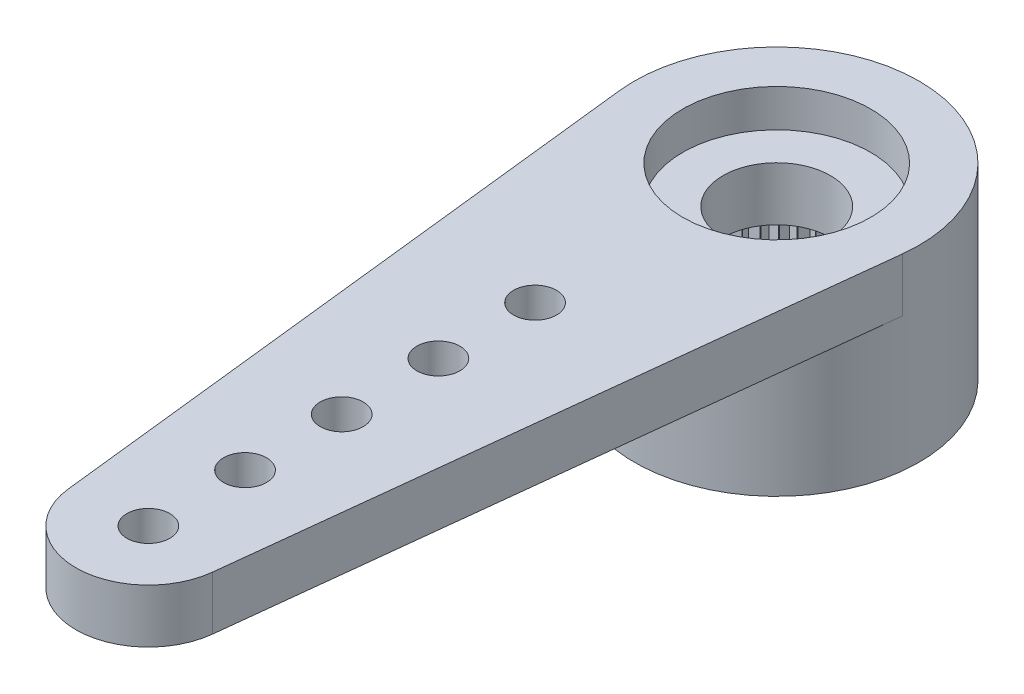
SolidWorks part; units mm, degrees
ref_plane "Front Plane" through (0, 0, 0) normal (0, 0, 1) x (1, 0, 0)
ref_plane "Top Plane" through (0, 0, 0) normal (0, 1, 0) x (1, 0, 0)
ref_plane "Right Plane" through (0, 0, 0) normal (1, 0, 0) x (0, 0, -1)
sketch "Sketch1" plane through (0, 0, 0) normal (0, 1, 0) x (1, 0, 0)
  line L0 (0, 0) -> (0, -14.859) construction
  line L1 (-1.7039, -15.0495) -> (-3.3447, -0.3739)
  line L2 (1.7039, -15.0495) -> (3.3447, -0.3739)
  arc A0 (3.3447, -0.3739) -> (-3.3447, -0.3739) centre (0, 0) ccw
  arc A1 (-1.7039, -15.0495) -> (1.7039, -15.0495) centre (0, -14.859) ccw
  dimension "D1" = 6.731
  dimension "D2" = 3.429
  dimension "D3" = 19.939
extrude "Boss-Extrude1" add sketch "Sketch1" along normal blind 1.27
sketch "Sketch2" plane through (0, 0, 0) normal (0, -1, 0) x (1, 0, 0)
  circle A0 centre (0, 0) radius 3.3655
extrude "Boss-Extrude2" add sketch "Sketch2" along normal blind 3.175
sketch "Sketch3" plane through (0, -3.175, 0) normal (0, -1, 0) x (-1, 0, 0)
  line L0 (0.3447, 2.4524) -> (0.1605, 2.2167)
  line L1 (0, 2.4765) -> (-0.1496, 2.2175)
  line L2 (0.4567, 2.1751) -> (0.3447, 2.4524)
  line L3 (0.1496, 2.2175) -> (0, 2.4765)
  line L4 (0.6826, 2.3806) -> (0.4675, 2.1728)
  line L5 (0.755, 2.0903) -> (0.6826, 2.3806)
  line L6 (1.0073, 2.2624) -> (0.7653, 2.0866)
  line L7 (1.0385, 1.9649) -> (1.0073, 2.2624)
  line L8 (1.3123, 2.1002) -> (1.0482, 1.9598)
  line L9 (1.3019, 1.8013) -> (1.3123, 2.1002)
  line L10 (1.5919, 1.8971) -> (1.3108, 1.7948)
  line L11 (1.5399, 1.6025) -> (1.5919, 1.8971)
  line L12 (1.8404, 1.6571) -> (1.5478, 1.5949)
  line L13 (1.748, 1.3726) -> (1.8404, 1.6571)
  line L14 (2.0531, 1.3848) -> (1.7547, 1.364)
  line L15 (1.922, 1.116) -> (2.0531, 1.3848)
  line L16 (2.2259, 1.0856) -> (1.9275, 1.1065)
  line L17 (2.0586, 0.8377) -> (2.2259, 1.0856)
  line L18 (2.3553, 0.7653) -> (2.0627, 0.8275)
  line L19 (2.1551, 0.543) -> (2.3553, 0.7653)
  line L20 (2.4389, 0.43) -> (2.1578, 0.5323)
  line L21 (2.2097, 0.2378) -> (2.4389, 0.43)
  line L22 (2.475, 0.0864) -> (2.2109, 0.2269)
  line L23 (2.2213, -0.0721) -> (2.475, 0.0864)
  line L24 (2.4629, -0.2589) -> (2.2209, -0.0831)
  line L25 (2.1897, -0.3805) -> (2.4629, -0.2589)
  line L26 (2.4029, -0.5991) -> (2.1878, -0.3913)
  line L27 (2.1154, -0.6816) -> (2.4029, -0.5991)
  line L28 (2.2962, -0.9277) -> (2.112, -0.692)
  line L29 (2, -0.9693) -> (2.2962, -0.9277)
  line L30 (2.1447, -1.2383) -> (1.9952, -0.9792)
  line L31 (1.8456, -1.2382) -> (2.1447, -1.2383)
  line L32 (1.9515, -1.5247) -> (1.8395, -1.2474)
  line L33 (1.6553, -1.4831) -> (1.9515, -1.5247)
  line L34 (1.7203, -1.7814) -> (1.648, -1.4912)
  line L35 (1.4328, -1.699) -> (1.7203, -1.7814)
  line L36 (1.4557, -2.0035) -> (1.4244, -1.7061)
  line L37 (1.1824, -1.8819) -> (1.4557, -2.0035)
  line L38 (1.1626, -2.1866) -> (1.1731, -1.8877)
  line L39 (0.909, -2.0281) -> (1.1626, -2.1866)
  line L40 (0.847, -2.3271) -> (0.899, -2.0326)
  line L41 (0.6179, -2.1349) -> (0.847, -2.3271)
  line L42 (0.5149, -2.4224) -> (0.6073, -2.1379)
  line L43 (0.3147, -2.2001) -> (0.5149, -2.4224)
  line L44 (0.1728, -2.4705) -> (0.3039, -2.2016)
  line L45 (-0.22, 2.0955) -> (0, 2.0955) [skipped]
  line L46 (0.0055, -2.2225) -> (0.1728, -2.4705)
  line L47 (-0.1728, -2.4705) -> (-0.0055, -2.2225)
  line L48 (-0.3039, -2.2016) -> (-0.1728, -2.4705)
  line L49 (-0.5149, -2.4224) -> (-0.3147, -2.2001)
  line L50 (-0.6073, -2.1379) -> (-0.5149, -2.4224)
  line L51 (-0.847, -2.3271) -> (-0.6179, -2.1349)
  line L52 (-0.899, -2.0326) -> (-0.847, -2.3271)
  line L53 (-1.1626, -2.1866) -> (-0.909, -2.0281)
  line L54 (-1.1731, -1.8877) -> (-1.1626, -2.1866)
  line L55 (-1.4557, -2.0035) -> (-1.1824, -1.8819)
  line L56 (-1.4244, -1.7061) -> (-1.4557, -2.0035)
  line L57 (-1.7203, -1.7814) -> (-1.4328, -1.699)
  line L58 (-1.648, -1.4912) -> (-1.7203, -1.7814)
  line L59 (-1.9515, -1.5247) -> (-1.6553, -1.4831)
  line L60 (-1.8395, -1.2474) -> (-1.9515, -1.5247)
  line L61 (-2.1447, -1.2382) -> (-1.8456, -1.2383)
  line L62 (-1.9952, -0.9792) -> (-2.1447, -1.2382)
  line L63 (-2.2962, -0.9277) -> (-2, -0.9693)
  line L64 (-2.112, -0.692) -> (-2.2962, -0.9277)
  line L65 (-2.4029, -0.5991) -> (-2.1154, -0.6816)
  line L66 (-2.1878, -0.3913) -> (-2.4029, -0.5991)
  line L67 (-2.4629, -0.2589) -> (-2.1897, -0.3805)
  line L68 (-2.2209, -0.0831) -> (-2.4629, -0.2589)
  line L69 (-2.475, 0.0864) -> (-2.2213, -0.0721)
  line L70 (-2.2109, 0.2269) -> (-2.475, 0.0864)
  line L71 (-2.4389, 0.43) -> (-2.2097, 0.2378)
  line L72 (-2.1578, 0.5323) -> (-2.4389, 0.43)
  line L73 (-2.3553, 0.7653) -> (-2.1551, 0.543)
  line L74 (-2.0627, 0.8275) -> (-2.3553, 0.7653)
  line L75 (-2.2259, 1.0856) -> (-2.0586, 0.8377)
  line L76 (-1.9275, 1.1065) -> (-2.2259, 1.0856)
  line L77 (-2.0531, 1.3848) -> (-1.922, 1.116)
  line L78 (-1.7547, 1.364) -> (-2.0531, 1.3848)
  line L79 (-1.8404, 1.6571) -> (-1.748, 1.3726)
  line L80 (-1.5478, 1.5949) -> (-1.8404, 1.6571)
  line L81 (-1.5919, 1.8971) -> (-1.5399, 1.6025)
  line L82 (-1.3108, 1.7948) -> (-1.5919, 1.8971)
  line L83 (-1.3123, 2.1002) -> (-1.3019, 1.8013)
  line L84 (-1.0482, 1.9598) -> (-1.3123, 2.1002)
  line L85 (-1.0073, 2.2624) -> (-1.0385, 1.9649)
  line L86 (-0.7653, 2.0866) -> (-1.0073, 2.2624)
  line L87 (-0.6826, 2.3806) -> (-0.755, 2.0903)
  line L88 (-0.4675, 2.1728) -> (-0.6826, 2.3806)
  line L89 (-0.3447, 2.4524) -> (-0.4567, 2.1751)
  line L90 (-0.1605, 2.2167) -> (-0.3447, 2.4524)
  arc A0 (-0.1496, 2.2175) -> (-0.1605, 2.2167) centre (0, 0) ccw
  circle A1 centre (0, 2.2225) radius 0.127 construction
  arc A2 (0.1605, 2.2167) -> (0.1496, 2.2175) centre (0, 0) ccw
  arc A3 (0.4675, 2.1728) -> (0.4567, 2.1751) centre (0, 0) ccw
  arc A4 (0.7653, 2.0866) -> (0.755, 2.0903) centre (0, 0) ccw
  arc A5 (1.0482, 1.9598) -> (1.0385, 1.9649) centre (0, 0) ccw
  arc A6 (1.3108, 1.7948) -> (1.3019, 1.8013) centre (0, 0) ccw
  arc A7 (1.5478, 1.5949) -> (1.5399, 1.6025) centre (0, 0) ccw
  arc A8 (1.7547, 1.364) -> (1.748, 1.3726) centre (0, 0) ccw
  arc A9 (1.9275, 1.1065) -> (1.922, 1.116) centre (0, 0) ccw
  arc A10 (-0.4567, 2.1751) -> (-0.4675, 2.1728) centre (0, 0) ccw
  arc A11 (-0.755, 2.0903) -> (-0.7653, 2.0866) centre (0, 0) ccw
  arc A12 (-1.0385, 1.9649) -> (-1.0482, 1.9598) centre (0, 0) ccw
  arc A13 (-1.3019, 1.8013) -> (-1.3108, 1.7948) centre (0, 0) ccw
  arc A14 (-1.5399, 1.6025) -> (-1.5478, 1.5949) centre (0, 0) ccw
  arc A15 (-1.748, 1.3726) -> (-1.7547, 1.364) centre (0, 0) ccw
  arc A16 (-1.922, 1.116) -> (-1.9275, 1.1065) centre (0, 0) ccw
  arc A17 (-2.0586, 0.8377) -> (-2.0627, 0.8275) centre (0, 0) ccw
  arc A18 (-2.1551, 0.543) -> (-2.1578, 0.5323) centre (0, 0) ccw
  arc A19 (-2.2097, 0.2378) -> (-2.2109, 0.2269) centre (0, 0) ccw
  arc A20 (-2.2213, -0.0721) -> (-2.2209, -0.0831) centre (0, 0) ccw
  arc A21 (2.0627, 0.8275) -> (2.0586, 0.8377) centre (0, 0) ccw
  arc A22 (2.1578, 0.5323) -> (2.1551, 0.543) centre (0, 0) ccw
  arc A23 (2.2109, 0.2269) -> (2.2097, 0.2378) centre (0, 0) ccw
  arc A24 (2.2209, -0.0831) -> (2.2213, -0.0721) centre (0, 0) ccw
  arc A25 (2.1878, -0.3913) -> (2.1897, -0.3805) centre (0, 0) ccw
  arc A26 (2.112, -0.692) -> (2.1154, -0.6816) centre (0, 0) ccw
  arc A27 (1.9952, -0.9792) -> (2, -0.9693) centre (0, 0) ccw
  arc A28 (1.8395, -1.2474) -> (1.8456, -1.2382) centre (0, 0) ccw
  arc A29 (1.648, -1.4912) -> (1.6553, -1.4831) centre (0, 0) ccw
  arc A30 (1.4244, -1.7061) -> (1.4328, -1.699) centre (0, 0) ccw
  arc A31 (1.1731, -1.8877) -> (1.1824, -1.8819) centre (0, 0) ccw
  arc A32 (0.899, -2.0326) -> (0.909, -2.0281) centre (0, 0) ccw
  arc A33 (0.6073, -2.1379) -> (0.6179, -2.1349) centre (0, 0) ccw
  arc A34 (0.3039, -2.2016) -> (0.3147, -2.2001) centre (0, 0) ccw
  arc A35 (-0.0055, -2.2225) -> (0.0055, -2.2225) centre (0, 0) ccw
  arc A36 (-0.3147, -2.2001) -> (-0.3039, -2.2016) centre (0, 0) ccw
  arc A37 (-0.6179, -2.1349) -> (-0.6073, -2.1379) centre (0, 0) ccw
  arc A38 (-0.909, -2.0281) -> (-0.899, -2.0326) centre (0, 0) ccw
  arc A39 (-1.1824, -1.8819) -> (-1.1731, -1.8877) centre (0, 0) ccw
  arc A40 (-1.4328, -1.699) -> (-1.4244, -1.7061) centre (0, 0) ccw
  arc A41 (-1.6553, -1.4831) -> (-1.648, -1.4912) centre (0, 0) ccw
  arc A42 (-1.8456, -1.2383) -> (-1.8395, -1.2474) centre (0, 0) ccw
  arc A43 (-2, -0.9693) -> (-1.9952, -0.9792) centre (0, 0) ccw
  arc A44 (-2.1154, -0.6816) -> (-2.112, -0.692) centre (0, 0) ccw
  arc A45 (-2.1897, -0.3805) -> (-2.1878, -0.3913) centre (0, 0) ccw
  point P145 (0, 0)
  dimension "D1" = 4.445
  dimension "D2" = 0.254
  dimension "D3" = 45
extrude "Cut-Extrude1" cut sketch "Sketch3" against normal blind 2.286
sketch "Sketch4" plane through (0, 1.27, 0) normal (0, 1, 0) x (1, 0, 0)
  circle A0 centre (0, 0) radius 2.2225
  dimension "D1" = 4.445
extrude "Cut-Extrude2" cut sketch "Sketch4" against normal blind 0.889
sketch "Sketch5" plane through (0, 0.381, 0) normal (0, 1, 0) x (1, 0, 0)
  circle A0 centre (0, 0) radius 1.27
  dimension "D1" = 2.54
extrude "Cut-Extrude3" cut sketch "Sketch5" against normal up to next
sketch "Sketch6" plane through (0, 1.27, 0) normal (0, 1, 0) x (1, 0, 0)
  line L0 (0, 0) -> (0, -14.859) construction
  circle A0 centre (0, -14.859) radius 0.508
  circle A1 centre (0, -12.573) radius 0.508
  circle A2 centre (0, -10.287) radius 0.508
  circle A3 centre (0, -8.001) radius 0.508
  circle A4 centre (0, -5.715) radius 0.508
  dimension "D1" = 1.016
  dimension "D2" = 1.016
  dimension "D3" = 1.27
  dimension "D4" = 1.27
  dimension "D5" = 1.27
  dimension "D6" = 1.27
extrude "Cut-Extrude4" cut sketch "Sketch6" against normal up to next
scale "Scale1" bodies to scale 106 scale about centroid uniform scaling yes scale factor 1.5
